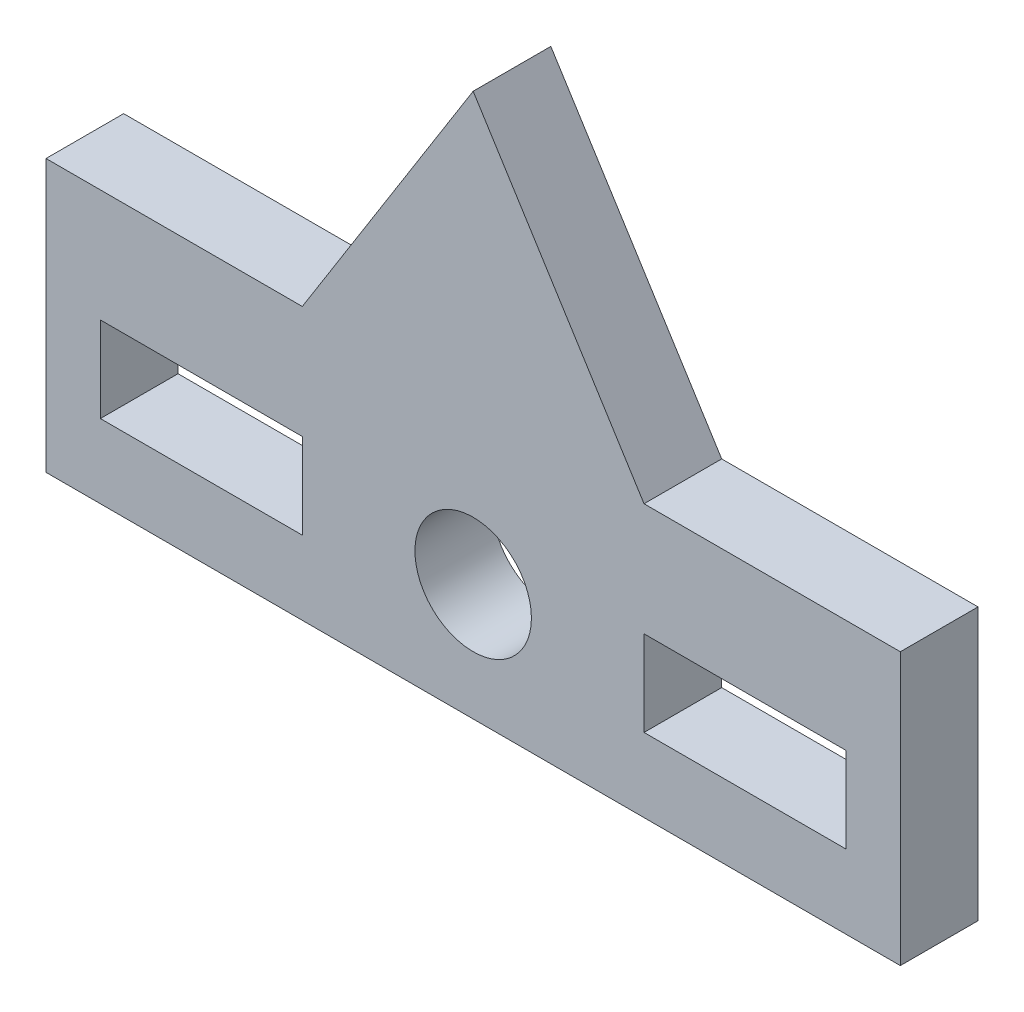
SolidWorks part; units mm, degrees
ref_plane "前视基准面" through (0, 0, 0) normal (0, 0, 1) x (1, 0, 0)
ref_plane "上视基准面" through (0, 0, 0) normal (0, 1, 0) x (1, 0, 0)
ref_plane "右视基准面" through (0, 0, 0) normal (1, 0, 0) x (0, 0, -1)
sketch "草图1" plane through (0, 0, 0) normal (0, 0, 1) x (1, 0, 0)
  line L0 (1.5, 0) -> (4.5, 0) construction
  line L1 (4.5, 0) -> (7, 0) construction
  line L2 (0, 0) -> (0, 11) construction
  line L3 (9.6, 1.1) -> (4.4, 1.1)
  line L4 (9.6, 1.1) -> (9.6, -1.1)
  line L5 (9.6, -1.1) -> (4.4, -1.1)
  line L6 (4.4, 1.1) -> (4.4, -1.1)
  line L7 (9.6, 1.1) -> (4.4, -1.1) construction
  line L8 (9.6, -1.1) -> (4.4, 1.1) construction
  line L9 (-9.6, -1.1) -> (-4.4, 1.1) construction
  line L10 (-9.6, 1.1) -> (-4.4, -1.1) construction
  line L11 (-4.5, 0) -> (-7, 0) construction
  line L12 (-4.4, 1.1) -> (-4.4, -1.1)
  line L13 (-9.6, -1.1) -> (-4.4, -1.1)
  line L14 (-9.6, 1.1) -> (-9.6, -1.1)
  line L15 (-9.6, 1.1) -> (-4.4, 1.1)
  line L16 (0, 0) -> (-11, 0) construction
  line L18 (-11, 0) -> (-11, -3)
  line L19 (-11, -3) -> (11, -3)
  line L20 (11, 0) -> (11, -3)
  line L22 (-11, 0) -> (-11, 4)
  line L23 (-11, 4) -> (-4.4, 4)
  line L28 (4.4, 4) -> (11, 4)
  line L29 (11, 4) -> (11, 0)
  line L41 (-4.4, 4) -> (0, 11)
  line L42 (0, 11) -> (4.4, 4)
  circle A0 centre (0, 0) radius 1.5
  point P21 (0, -3)
extrude "凸台-拉伸1" add sketch "草图1" along normal blind 2
sketch "草图2" plane through (11, 0, 0) normal (1, 0, 0) x (0, 0, -1)
  line L0 (-1, 4) -> (-1, 11)
  line L1 (-2, 4) -> (0, 4) construction
  line L2 (-2, 11) -> (0, 11) construction
  line L3 (-1, 11) -> (0, 4)
  line L4 (0, 4) -> (0, 11)
  line L5 (0, 11) -> (-2, 11)
  line L6 (-2, 11) -> (-2, 4)
  line L7 (-2, 4) -> (-1, 11)
extrude "切除-拉伸1" [suppressed] cut sketch "草图2" against normal blind 20 contours L6 L7 L5 | L4 L5 L3
